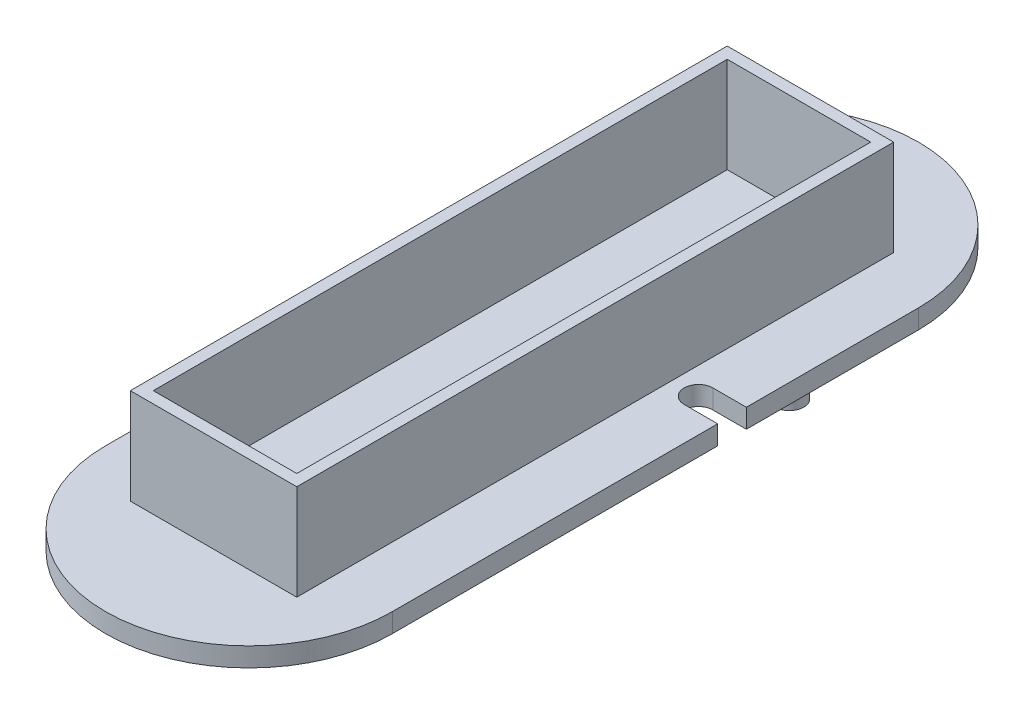
SolidWorks part; units mm, degrees
material "Acrylic (Medium-high impact)"
ref_plane "Front Plane" through (0, 0, 0) normal (0, 0, 1) x (1, 0, 0)
ref_plane "Top Plane" through (0, 0, 0) normal (0, 1, 0) x (1, 0, 0)
ref_plane "Right Plane" through (0, 0, 0) normal (1, 0, 0) x (0, 0, -1)
sketch "Plate Sketch" plane through (0, 0, 0) normal (0, 1, 0) x (1, 0, 0)
  line L0 (11.5, 0) -> (-11.5, 0) construction
  line L1 (0, 10) -> (0, -45) construction
  line L2 (15, 10) -> (15, -8)
  line L3 (-15, 10) -> (-15, -8)
  line L4 (-11.5, -8) -> (-15, -8)
  line L5 (-11.5, -11) -> (-15, -11)
  line L6 (15, -8) -> (11.5, -8)
  line L7 (11.5, -11) -> (15, -11)
  line L8 (-15, -11) -> (-15, -45)
  line L9 (15, -11) -> (15, -45)
  circle A0 centre (-11.5, 0) radius 1.5 construction
  circle A1 centre (11.5, 0) radius 1.5 construction
  arc A2 (15, 10) -> (-15, 10) centre (0, 10) ccw
  arc A3 (-15, -45) -> (15, -45) centre (0, -45) ccw
  arc A4 (-11.5, -11) -> (-11.5, -8) centre (-11.5, -9.5) ccw
  arc A5 (11.5, -8) -> (11.5, -11) centre (11.5, -9.5) ccw
  point P4 (0, 0)
  dimension "Peg" = 3
  dimension "Hole Diameter" = 3
  dimension "Peg Spacing" = 23
  dimension "Peg to Edge" = 2
  dimension "D1" = 25
  dimension "D2" = 60
  dimension "Peg to Hole" = 9.5
extrude "Plate Extrude" add sketch "Plate Sketch" along normal blind 2
sketch "Peg Sketch" plane through (0, 0, 0) normal (0, -1, 0) x (1, 0, 0)
  circle A0 centre (11.5, 0) radius 1.5 construction
  circle A1 centre (-11.5, 0) radius 1.5 construction
  circle A2 centre (11.5, 0) radius 1.5
  circle A3 centre (-11.5, 0) radius 1.5
extrude "Peg Extrude" add sketch "Peg Sketch" along normal blind 3
sketch "Sketch3" plane through (0, 2, 0) normal (0, 1, 0) x (1, 0, 0)
  line L0 (0, 25) -> (0, -60) construction
  line L1 (-7.5, -47.5) -> (7.5, -47.5)
  line L2 (-7.5, -47.5) -> (-7.5, 12.5)
  line L3 (-7.5, 12.5) -> (7.5, 12.5)
  line L4 (7.5, -47.5) -> (7.5, 12.5)
  line L5 (-7.5, -47.5) -> (7.5, 12.5) construction
  line L6 (-7.5, 12.5) -> (7.5, -47.5) construction
  line L7 (-8.7, 13.7) -> (8.7, 13.7)
  line L8 (8.7, -48.7) -> (8.7, 13.7)
  line L9 (-8.7, -48.7) -> (8.7, -48.7)
  line L10 (-8.7, -48.7) -> (-8.7, 13.7)
  arc A0 (15, 10) -> (-15, 10) centre (0, 10) ccw construction
  arc A1 (-15, -45) -> (15, -45) centre (0, -45) ccw construction
  point P0 (0, -17.5)
  point P5 (0, -17.5)
  dimension "Width" = 15
  dimension "Length" = 60
  dimension "D1" = 1.2
extrude "Boss-Extrude3" add sketch "Sketch3" along normal blind 10
equation "\"Peg Diameter\"= 3"
equation "\"Peg Spacing\"= 23"
equation "\"Peg@Plate Sketch\" = \"Peg Diameter\""
equation "\"Peg Spacing@Plate Sketch\" = \"Peg Spacing\""
equation "\"Peg to Edge Distance\"=2"
equation "\"Peg to Edge@Plate Sketch\" = \"Peg to Edge Distance\""
equation "\"Peg to Hole Distance\"= 9.5"
equation "\"Hole Diameter\"=3"
equation "\"Hole Diameter@Plate Sketch\" = \"Hole Diameter\""
equation "\"Peg to Hole@Plate Sketch\" = \"Peg to Hole Distance\""
equation "\"Peg Length\"= 3"
equation "\"Peg Length@Peg Extrude\" = \"Peg Length\""
equation "\"Battery Wall Length\"= 60"
equation "\"Battery Wall Width\"= 15"
equation "\"Battery Wall Height\"= 10"
equation "\"Width@Sketch3\" = \"Battery Wall Width\""
equation "\"Length@Sketch3\" = \"Battery Wall Length\""
equation "\"Battery Wall Thickness\"= 1.2"
equation "\"D1@Boss-Extrude3\"=\"Battery Wall Height\""
